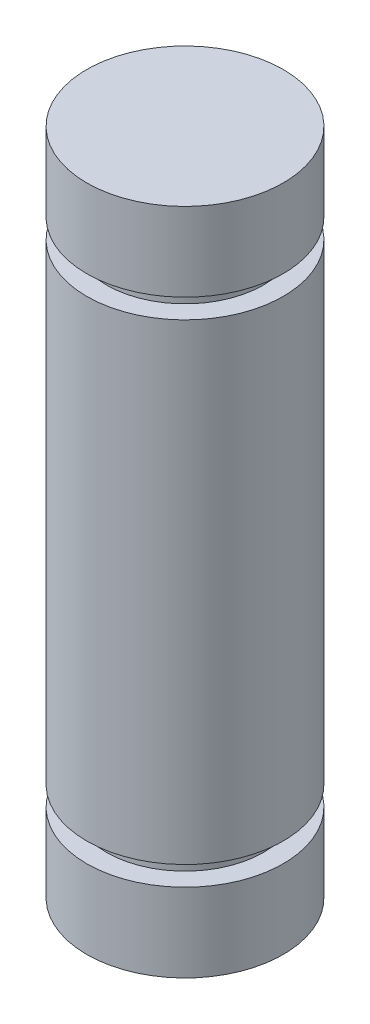
SolidWorks part; units mm, degrees
ref_plane "Front Plane" through (0, 0, 0) normal (0, 0, 1) x (1, 0, 0)
ref_plane "Top Plane" through (0, 0, 0) normal (0, 1, 0) x (1, 0, 0)
ref_plane "Right Plane" through (0, 0, 0) normal (1, 0, 0) x (0, 0, -1)
sketch "Sketch1" plane through (0, 0, 0) normal (0, 1, 0) x (1, 0, 0)
  circle A0 centre (0, 0) radius 6.35
  dimension "D1" = 12.7
extrude "Boss-Extrude2" add sketch "Sketch1" along normal blind 30.48
sketch "Sketch4" plane through (0, 30.48, 0) normal (0, 1, 0) x (1, 0, 0)
  circle A0 centre (0, 0) radius 5.08
  dimension "D1" = 10.16
extrude "Boss-Extrude3" add sketch "Sketch4" along normal blind 1.27
sketch "Sketch5" plane through (0, 31.75, 0) normal (0, 1, 0) x (1, 0, 0)
  circle A0 centre (0, 0) radius 6.35
  dimension "D1" = 12.7
extrude "Boss-Extrude4" add sketch "Sketch5" along normal blind 5.08
sketch "Sketch6" plane through (0, 0, 0) normal (0, -1, 0) x (1, 0, 0)
  circle A0 centre (0, 0) radius 5.08
  dimension "D1" = 10.16
extrude "Boss-Extrude5" add sketch "Sketch6" along normal blind 1.27
sketch "Sketch7" plane through (0, -1.27, 0) normal (0, -1, 0) x (1, 0, 0)
  circle A0 centre (0, 0) radius 6.35
  dimension "D1" = 12.7
extrude "Boss-Extrude6" add sketch "Sketch7" along normal blind 5.08
